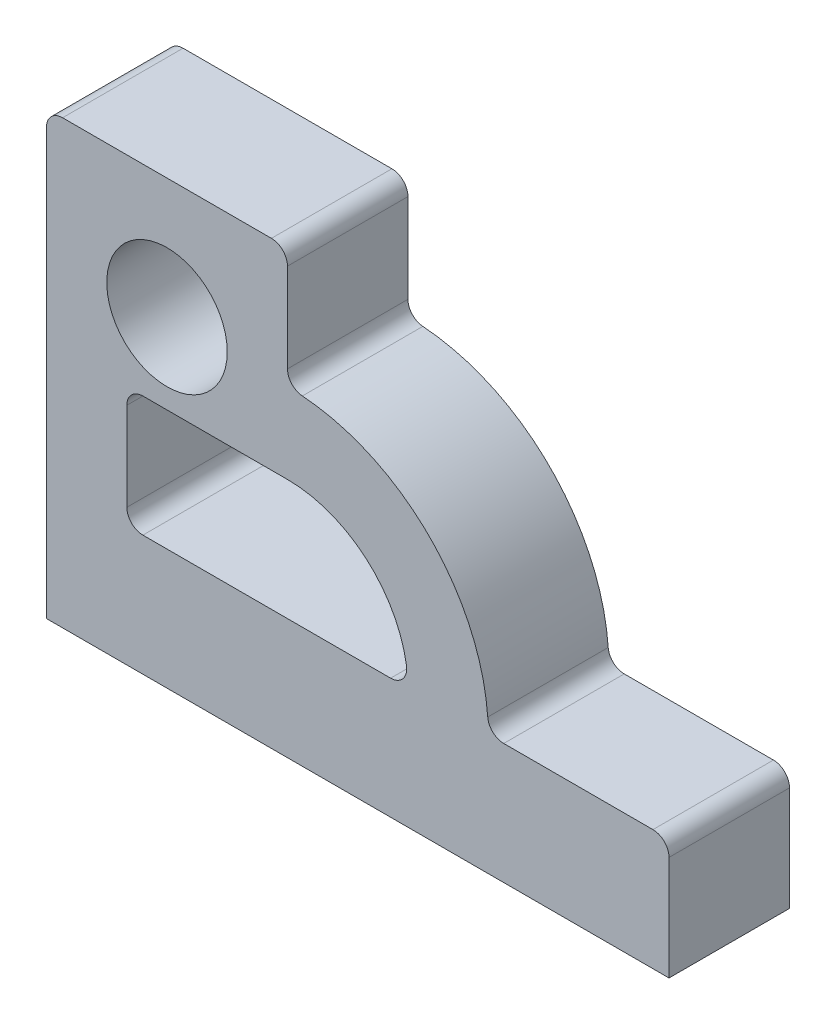
SolidWorks part; units mm, degrees
ref_plane "Front Plane" through (0, 0, 0) normal (0, 0, 1) x (1, 0, 0)
ref_plane "Top Plane" through (0, 0, 0) normal (0, 1, 0) x (1, 0, 0)
ref_plane "Right Plane" through (0, 0, 0) normal (1, 0, 0) x (0, 0, -1)
sketch "Sketch1" plane through (0, 0, 0) normal (0, 0, 1) x (1, 0, 0)
  line L0 (0, 0) -> (0, -106802.4658) construction
  line L1 (0, 0) -> (-106802.4658, 0) construction
  line L2 (0, 0) -> (0, 106)
  line L3 (4, 110) -> (56, 110)
  line L4 (60, 106) -> (60, 83.8516)
  line L5 (113.8516, 30) -> (151, 30)
  line L6 (155, 26) -> (155, 0)
  line L7 (155, 0) -> (0, 0)
  line L8 (85.6905, 30) -> (24, 30)
  line L9 (20, 34) -> (20, 56)
  line L10 (24, 60) -> (60, 60)
  arc A0 (63.7037, 79.8626) -> (109.8626, 33.7037) centre (60, 30) cw
  arc A1 (60, 60) -> (89.6428, 34.6154) centre (60, 30) cw
  circle A2 centre (30, 80) radius 15
  arc A3 (20, 56) -> (24, 60) centre (24, 56) cw
  arc A4 (24, 30) -> (20, 34) centre (24, 34) cw
  arc A5 (151, 30) -> (155, 26) centre (151, 26) cw
  arc A6 (85.6905, 30) -> (89.6428, 34.6154) centre (85.6905, 34) ccw
  arc A7 (109.8626, 33.7037) -> (113.8516, 30) centre (113.8516, 34) ccw
  arc A8 (60, 83.8516) -> (63.7037, 79.8626) centre (64, 83.8516) ccw
  arc A9 (56, 110) -> (60, 106) centre (56, 106) cw
  arc A10 (0, 106) -> (4, 110) centre (4, 106) cw
  point P18 (0, 0)
  point P20 (0, 0)
  point P21 (-66.7618, 144.5383)
  point P22 (30, 110)
  point P25 (20, 60)
  point P28 (20, 30)
  point P41 (0, 110)
  dimension "D1" = 110
  dimension "D5" = 50
  dimension "D6" = 20
  dimension "D8" = 30
  dimension "D10" = 4
  dimension "D2" = 155
  dimension "D3" = 60
  dimension "D4" = 30
  dimension "D7" = 30
  dimension "D9" = 30
extrude "Boss-Extrude1" add sketch "Sketch1" along normal mid plane 30
